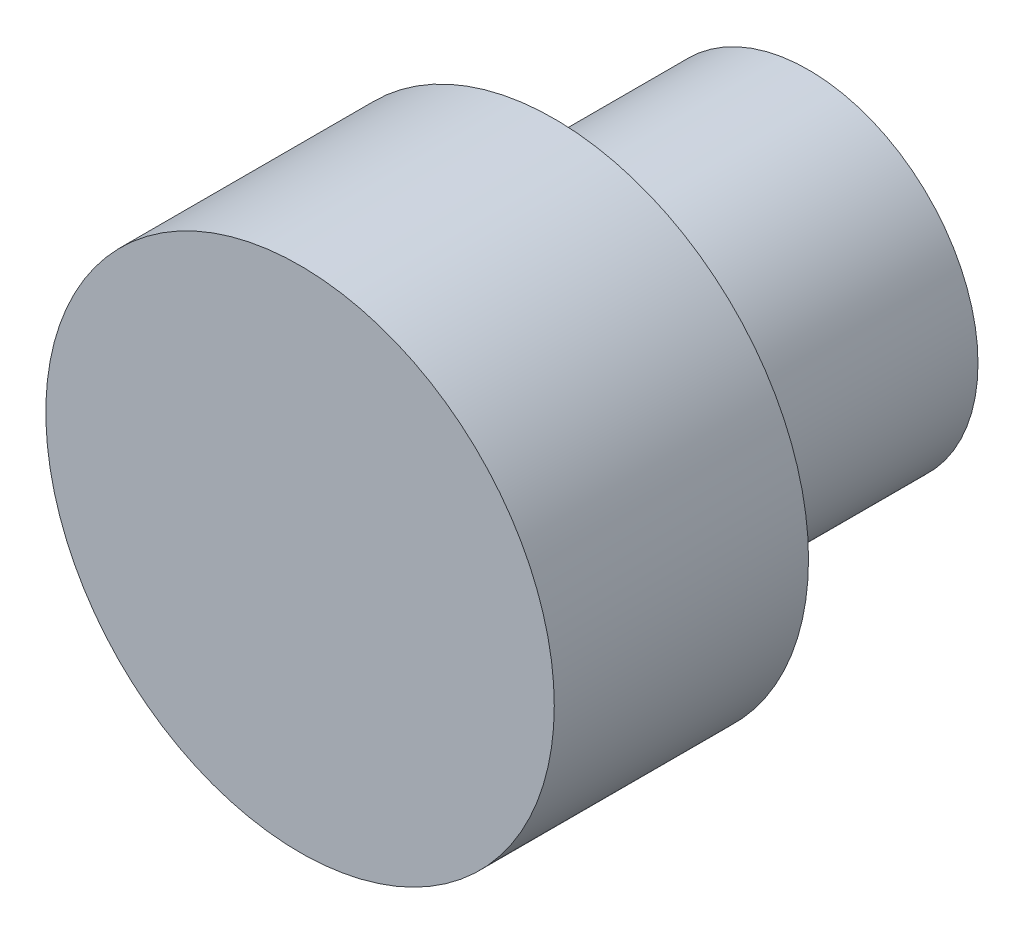
SolidWorks part; units mm, degrees
ref_plane "前视基准面" through (0, 0, 0) normal (0, 0, 1) x (1, 0, 0)
ref_plane "上视基准面" through (0, 0, 0) normal (0, 1, 0) x (1, 0, 0)
ref_plane "右视基准面" through (0, 0, 0) normal (1, 0, 0) x (0, 0, -1)
sketch "草图1" plane through (0, 0, 0) normal (1, 0, 0) x (0, 0, -1)
  line L0 (0, 0) -> (6, 0)
  line L1 (6, 0) -> (6, 2)
  line L2 (6, 2) -> (3, 2)
  line L3 (3, 2) -> (3, 3)
  line L4 (3, 3) -> (0, 3)
  line L5 (0, 3) -> (0, 0)
  dimension "D1" = 2
  dimension "D2" = 1
  dimension "D3" = 6
  dimension "D4" = 3
revolve "旋转1" add sketch "草图1" angle 360 about L0
